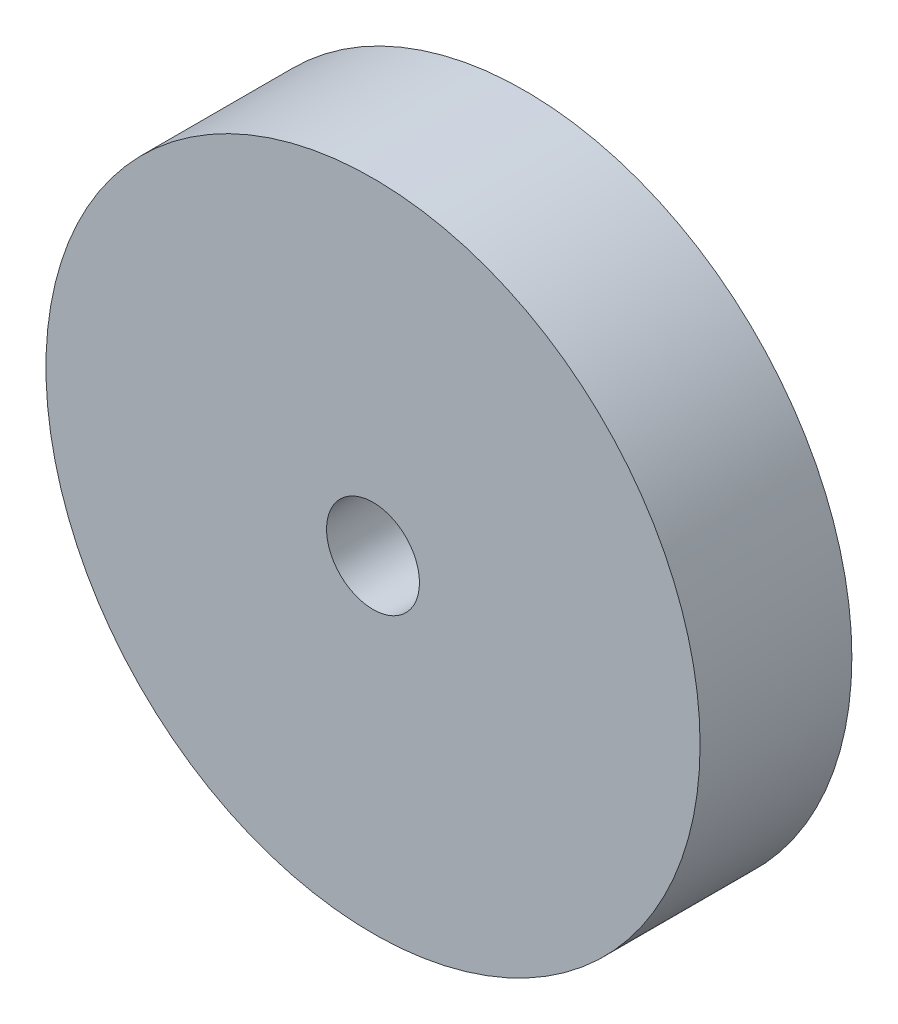
SolidWorks part; units mm, degrees
ref_plane "Front Plane" through (0, 0, 0) normal (0, 0, 1) x (1, 0, 0)
ref_plane "Top Plane" through (0, 0, 0) normal (0, 1, 0) x (1, 0, 0)
ref_plane "Right Plane" through (0, 0, 0) normal (1, 0, 0) x (0, 0, -1)
sketch "Sketch1" plane through (0, 0, 0) normal (0, 0, 1) x (1, 0, 0)
  circle A0 centre (0, 0) radius 21.55
  dimension "D1" = 43.1
extrude "Base" add sketch "Sketch1" along normal blind 10
sketch "Sketch2" plane through (0, 0, 10) normal (0, 0, 1) x (1, 0, 0)
  circle A0 centre (0, 0) radius 3.06
  dimension "D1" = 6.12
extrude "Cut-Extrude1" cut sketch "Sketch2" against normal through all
